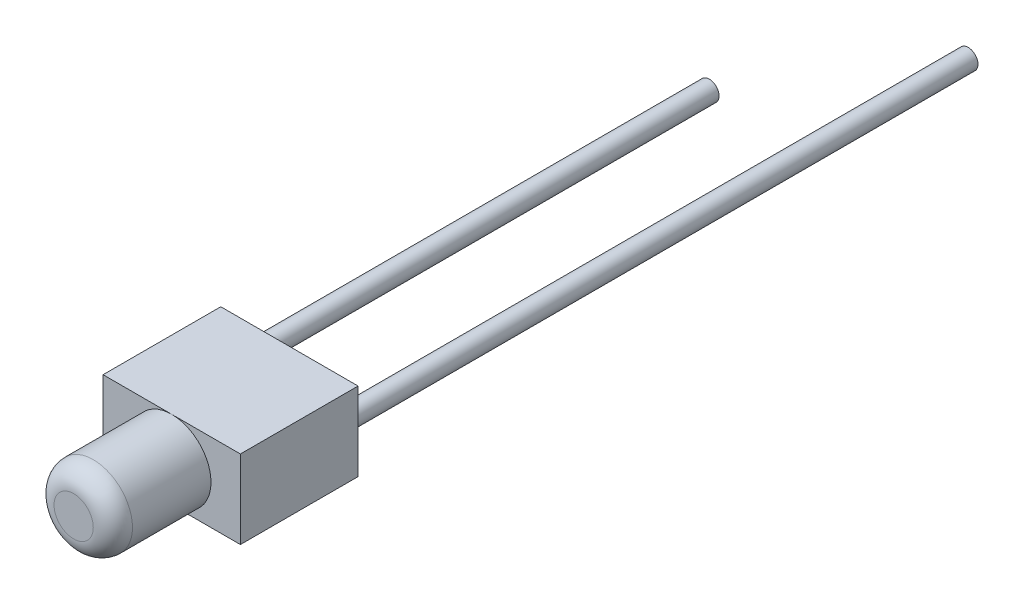
SolidWorks part; units mm, degrees
ref_plane "Plano frontal" through (0, 0, 0) normal (0, 0, 1) x (1, 0, 0)
ref_plane "Plano superior" through (0, 0, 0) normal (0, 1, 0) x (1, 0, 0)
ref_plane "Plano direito" through (0, 0, 0) normal (1, 0, 0) x (0, 0, -1)
sketch "Esboço1" plane through (0, 0, 0) normal (0, 0, 1) x (1, 0, 0)
  line L1 (0, 0) -> (3.5, 0)
  line L2 (0, 0) -> (0, -2)
  line L3 (0, -2) -> (3.5, -2)
  line L4 (3.5, 0) -> (3.5, -2)
  dimension "D1" = 2
  dimension "D2" = 3.5
extrude "Ressalto-extrusão1" add sketch "Esboço1" along normal blind 5.5
sketch "Esboço2" plane through (0, 0, 5.5) normal (0, 0, 1) x (1, 0, 0)
  line L0 (1.75, 0) -> (1.75, -2) construction
  line L1 (3.5, 0) -> (0, 0) construction
  line L2 (0, -2) -> (3.5, -2) construction
  line L4 (3.5, -2) -> (0, -2)
  line L5 (3.5, -2) -> (3.5, 0)
  line L6 (3.5, 0) -> (0, 0)
  line L7 (0, -2) -> (0, 0)
  line L8 (3.5, -2) -> (0, 0) construction
  line L9 (3.5, 0) -> (0, -2) construction
  circle A0 centre (1.75, -1) radius 1
  line M1 (0, 0) -> (0, -2)
  line M2 (0, -2) -> (3.5, -2)
  line M3 (3.5, -2) -> (3.5, 0)
  line M4 (3.5, 0) -> (0, 0)
extrude "Corte-extrusão1" cut sketch "Esboço2" against normal blind 2.5 contours A0 L6 M1 M2 | A0 L4 M3 M4
fillet "Filete1" radius 0.5 1 edges at (2.75, -1, 5.5)
sketch "Esboço3" plane through (0, 0, 0) normal (0, 0, -1) x (-1, 0, 0)
  line L0 (-3.5, -1) -> (0, -1) construction
  line L1 (-3.5, -2) -> (-3.5, 0) construction
  line L2 (0, 0) -> (0, -2) construction
  line L3 (-1.75, 0) -> (-1.75, -2) construction
  line L4 (-3.5, 0) -> (0, 0) construction
  circle A0 centre (-3.05, -1) radius 0.25
  circle A1 centre (-0.45, -1) radius 0.25
  dimension "D1" = 0.5
  dimension "D2" = 0.5
  dimension "D3" = 1.3
  dimension "D4" = 1.3
extrude "Ressalto-extrusão2" add sketch "Esboço3" along normal blind 16
sketch "Esboço4" plane through (0, 0, -16) normal (0, 0, -1) x (-1, 0, 0)
  circle A0 centre (-0.45, -1) radius 0.3509
  dimension "D1" = 0.7018
extrude "Corte-extrusão2" cut sketch "Esboço4" against normal blind 4
